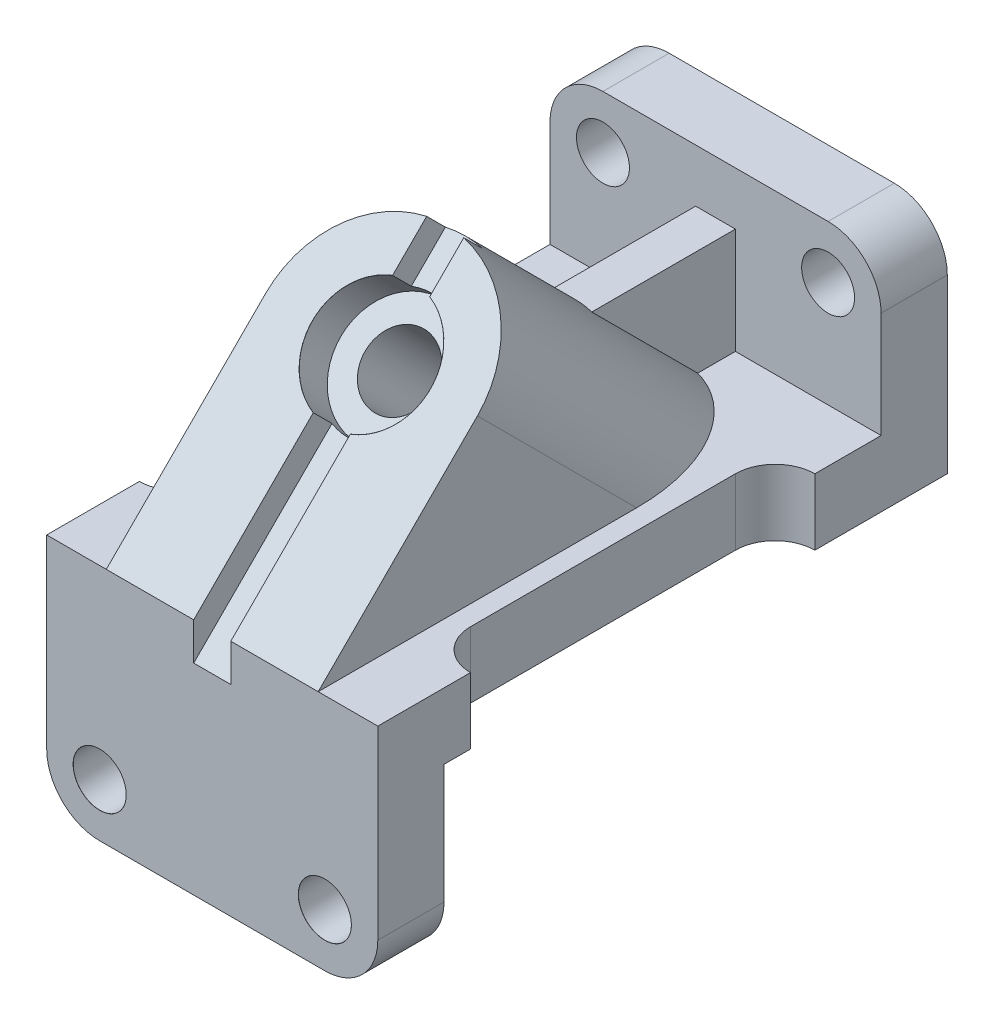
SolidWorks part; units mm, degrees
ref_plane "Front Plane" through (0, 0, 0) normal (0, 0, 1) x (1, 0, 0)
ref_plane "Top Plane" through (0, 0, 0) normal (0, 1, 0) x (1, 0, 0)
ref_plane "Right Plane" through (0, 0, 0) normal (1, 0, 0) x (0, 0, -1)
sketch "Sketch1" plane through (0, 0, 0) normal (1, 0, 0) x (0, 0, -1)
  line L0 (0, 0) -> (0, 90)
  line L1 (0, 90) -> (190, 90)
  line L2 (190, 90) -> (190, 150)
  line L3 (25, 0) -> (25, 65)
  line L4 (25, 65) -> (215, 65)
  line L5 (215, 65) -> (215, 150)
  line L6 (0, 0) -> (25, 0)
  line L7 (190, 150) -> (215, 150)
  dimension "D1" = 90
  dimension "D2" = 215
  dimension "D3" = 85
  dimension "D4" = 25
extrude "Boss-Extrude1" add sketch "Sketch1" against normal mid plane 125
ref_plane "Plane1" through (0, 45, 45) normal (0, 0.7071, 0.7071) x (1, 0, 0)
sketch "Sketch2" plane through (0, 45, 45) normal (0, 0.7071, 0.7071) x (1, 0, 0)
  line L0 (-40, 63.6396) -> (-40, 148.6396)
  line L1 (-62.5, 63.6396) -> (62.5, 63.6396) construction
  line L2 (40, 148.6396) -> (40, 63.6396)
  line L3 (40, 63.6396) -> (-40, 63.6396)
  arc A1 (-40, 148.6396) -> (40, 148.6396) centre (0, 148.6396) cw
  dimension "D1" = 85
  dimension "D2" = 40
extrude "Boss-Extrude2" add sketch "Sketch2" against normal up to surface (85 mm away) contours L3 L0 A1 L2
sketch "Sketch4" plane through (0, 45, 45) normal (0, 0.7071, 0.7071) x (1, 0, 0)
  point P0 (0, 148.6396)
hole_wizard "CBORE for M24 Hex Head Bolt1" positions "Sketch4" profile "Sketch5" counterbore size "M24" standard "ISO" end condition through all
sketch "Sketch5" plane through (0, 150.1041, -60.1041) normal (1, 0, 0) x (0, -0.7071, 0.7071)
  line L0 (0, 0) -> (0, 215.6676)
  line L1 (0, 215.6676) -> (13, 215.6676)
  line L3 (13, 215.6676) -> (13, 15)
  line L4 (22.2845, 15) -> (13, 15)
  line L5 (22.2845, 15) -> (22.2845, 0.025)
  line L6 (22.2845, 0.025) -> (22.3095, 0)
  line L7 (22.3095, 0) -> (0, 0)
  line L8 (-22.2845, 0.025) -> (-22.3095, 0) construction
  line L11 (0, -6.35) -> (0, 107.95) construction
  dimension "Thru Hole Dia." = 26
  dimension "Thru Hole Depth" = 215.6676
  dimension "C'Bore Dia." = 44.569
  dimension "C'Bore Depth" = 15
  dimension "Near C'Sink Dia." = 44.619
  dimension "Near C'Sink Angle" = 90
sketch "Sketch6" plane through (0, 45, 45) normal (0, 0.7071, 0.7071) x (1, 0, 0)
  line L1 (-7, 15.0679) -> (7, 15.0679)
  line L2 (-7, 15.0679) -> (-7, 282.2113)
  line L3 (-7, 282.2113) -> (7, 282.2113)
  line L4 (7, 15.0679) -> (7, 282.2113)
  line L5 (-7, 15.0679) -> (7, 282.2113) construction
  line L6 (-7, 282.2113) -> (7, 15.0679) construction
  point P0 (0, 148.6396)
  dimension "D1" = 14
extrude "Cut-Extrude1" cut sketch "Sketch6" against normal blind 10
sketch "Sketch7" plane through (0, 0, 0) normal (1, 0, 0) x (0, 0, -1)
  line L0 (136.7767, 130) -> (190, 130)
  line L1 (176.7767, 90) -> (95.4594, 171.3173) construction
  line L2 (190, 150) -> (190, 90) construction
  line L3 (190, 90) -> (0, 90) construction
  dimension "D1" = 40
rib "Rib1" sketch "Sketch7" sketch "Sketch7" thickness 15 extrusion direction parallel to sketch draft on no parameters "D1"=15
fillet "Fillet1" radius 20 4 edges at (-62.5, 0, -12.5) (62.5, 0, -12.5) (-62.5, 150, -202.5) (62.5, 150, -202.5)
sketch "Sketch8" plane through (0, 90, 0) normal (0, 1, 0) x (1, 0, 0)
  line L0 (62.5, 150) -> (62.5, 50) construction
  line L1 (62.5, 190) -> (62.5, 0) construction
  line L2 (77.5, 150) -> (77.5, 50)
  line L3 (47.5, 150) -> (47.5, 50)
  line L4 (40, 0) -> (62.5, 0) construction
  line L5 (0, 237.6587) -> (0, -32.0496) construction
  line L6 (-62.5, 150) -> (-62.5, 50) construction
  line L7 (-77.5, 150) -> (-77.5, 50)
  line L8 (-47.5, 150) -> (-47.5, 50)
  arc A0 (77.5, 150) -> (47.5, 150) centre (62.5, 150) ccw
  arc A1 (47.5, 50) -> (77.5, 50) centre (62.5, 50) ccw
  arc A2 (-77.5, 150) -> (-47.5, 150) centre (-62.5, 150) cw
  arc A3 (-47.5, 50) -> (-77.5, 50) centre (-62.5, 50) cw
  point P4 (62.5, 100)
  point P16 (-62.5, 100)
  dimension "D1" = 15
  dimension "D2" = 100
  dimension "D3" = 50
extrude "Cut-Extrude2" cut sketch "Sketch8" against normal blind 30
sketch "Sketch9" plane through (0, 0, 0) normal (0, 0, 1) x (1, 0, 0)
  line L0 (40, 90) -> (62.5, 90) construction
  point P0 (42.5, 20)
  point P2 (-42.5, 20)
  dimension "D1" = 85
  dimension "D2" = 42.5
  dimension "D3" = 70
hole_wizard "Ø20.0 (20) Diameter Hole1" positions "Sketch9" profile "Sketch10" hole size "Ø20.0" standard "ISO" end condition through all
sketch "Sketch10" plane through (42.5, 20, 0) normal (1, 0, 0) x (0, -1, 0)
  line L0 (0, 0) -> (0, 215)
  line L1 (0, 215) -> (10, 215)
  line L2 (10, 215) -> (10, 0.025)
  line L3 (10, 0.025) -> (10.025, 0)
  line L5 (10.025, 0) -> (0, 0)
  line L6 (-10, 0.025) -> (-10.025, 0) construction
  line L11 (0, -6.35) -> (0, 107.95) construction
  dimension "Thru Hole Dia." = 20
  dimension "Thru Hole Depth" = 215
  dimension "Near C'Sink Dia." = 20.05
  dimension "Near C'Sink Angle" = 90
sketch "Sketch13" plane through (0, 0, -215) normal (0, 0, -1) x (-1, 0, 0)
  line L0 (62.5, 65) -> (-62.5, 65) construction
  point P0 (-42.5, 130)
  point P2 (42.5, 130)
  dimension "D1" = 85
  dimension "D2" = 42.5
  dimension "D3" = 65
hole_wizard "Ø20.0 (20) Diameter Hole2" positions "Sketch13" profile "Sketch15" hole size "Ø20.0" standard "ISO"
sketch "Sketch15" plane through (42.5, 130, -215) normal (1, 0, 0) x (0, 1, 0)
  line L0 (0, 0) -> (0, 46.0086)
  line L1 (0, 46.0086) -> (10, 40)
  line L2 (10, 40) -> (10, 0.025)
  line L3 (10, 0.025) -> (10.025, 0)
  line L5 (10.025, 0) -> (0, 0)
  line L6 (-10, 0.025) -> (-10.025, 0) construction
  line L10 (0, 46.0086) -> (-10, 40) construction
  line L11 (0, -6.35) -> (0, 107.95) construction
  dimension "Hole Dia." = 20
  dimension "Hole Depth" = 40
  dimension "Near C'Sink Dia." = 20.05
  dimension "Near C'Sink Angle" = 90
  dimension "Drill Angle" = 118
